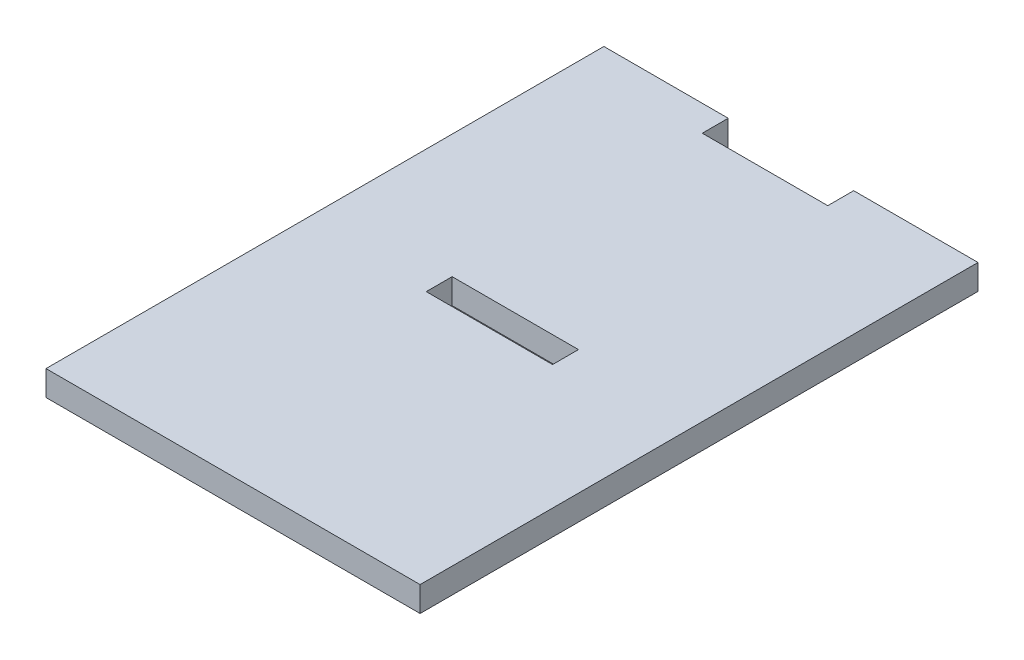
SolidWorks part; units mm, degrees
ref_plane "Front Plane" through (0, 0, 0) normal (0, 0, 1) x (1, 0, 0)
ref_plane "Top Plane" through (0, 0, 0) normal (0, 1, 0) x (1, 0, 0)
ref_plane "Right Plane" through (0, 0, 0) normal (1, 0, 0) x (0, 0, -1)
sketch "Sketch2" plane through (0, 0, 0) normal (0, 1, 0) x (1, 0, 0)
  line L0 (0, 33.345) -> (44.72, 33.345) construction
  line L29 (0, 0) -> (44.72, 0)
  line L30 (0, 0) -> (0, 66.69)
  line L65 (44.72, 0) -> (44.72, 66.69)
  line L66 (14.76, 33.79) -> (29.86, 33.79)
  line L67 (14.76, 33.79) -> (14.76, 30.69)
  line L68 (14.76, 30.69) -> (29.86, 30.69)
  line L69 (29.86, 33.79) -> (29.86, 30.69)
  line L74 (0, 66.69) -> (14.86, 66.69)
  line L76 (14.86, 66.69) -> (14.86, 63.59)
  line L77 (14.86, 63.59) -> (29.86, 63.59)
  line L78 (29.86, 66.69) -> (29.86, 63.59)
  line L79 (29.86, 66.69) -> (44.72, 66.69)
  dimension "D1" = 44.72
  dimension "D3" = 15.1
  dimension "D4" = 3.1
  dimension "D5" = 14.76
  dimension "D6" = 30.69
  dimension "D7" = 15
  dimension "D8" = 3.1
  dimension "D9" = 29.8
extrude "Boss-Extrude3" add sketch "Sketch2" along normal blind 3
